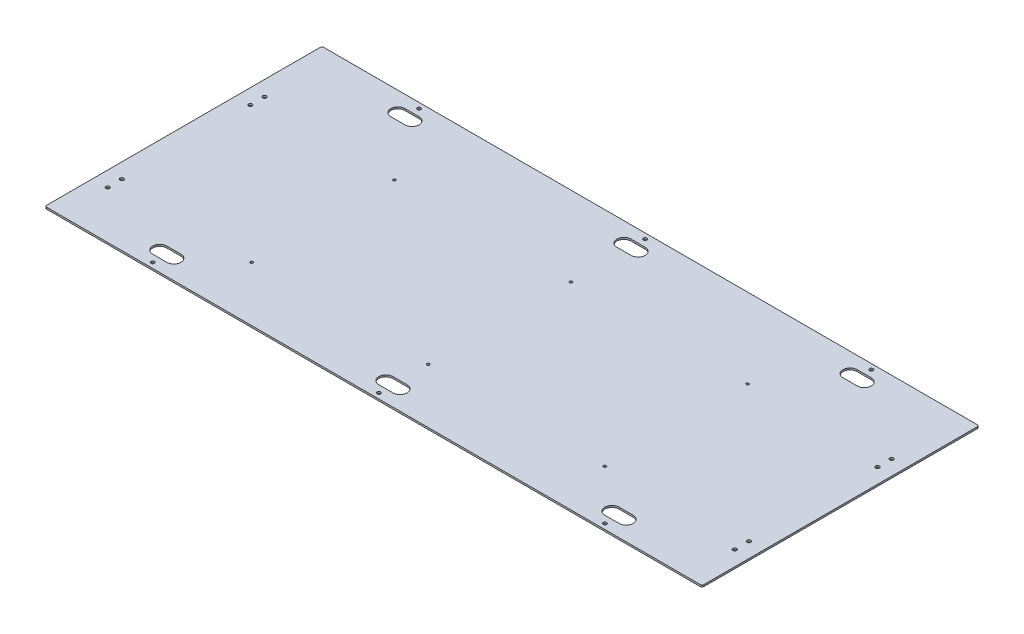
SolidWorks part; units mm, degrees
material "PE High Density"
ref_plane "Front Plane" through (0, 0, 0) normal (0, 0, 1) x (1, 0, 0)
ref_plane "Top Plane" through (0, 0, 0) normal (0, 1, 0) x (1, 0, 0)
ref_plane "Right Plane" through (0, 0, 0) normal (1, 0, 0) x (0, 0, -1)
sketch "Sketch1" plane through (0, 0, 0) normal (0, 1, 0) x (1, 0, 0)
  line L1 (-587.375, -248.92) -> (587.375, -248.92)
  line L2 (-590.55, -245.745) -> (-590.55, 245.745)
  line L3 (-587.375, 248.92) -> (587.375, 248.92)
  line L4 (590.55, -245.745) -> (590.55, 245.745)
  line L5 (-590.55, -248.92) -> (590.55, 248.92) construction
  line L6 (-590.55, 248.92) -> (590.55, -248.92) construction
  arc A0 (587.375, 248.92) -> (590.55, 245.745) centre (587.375, 245.745) cw
  arc A1 (587.375, -248.92) -> (590.55, -245.745) centre (587.375, -245.745) ccw
  arc A2 (-587.375, -248.92) -> (-590.55, -245.745) centre (-587.375, -245.745) cw
  arc A3 (-590.55, 245.745) -> (-587.375, 248.92) centre (-587.375, 245.745) cw
  point P0 (0, 0)
  dimension "D3" = 3.175
  dimension "D1" = 1181.1
  dimension "D2" = 497.84
extrude "Boss-Extrude1" add sketch "Sketch1" along normal blind 3.175
sketch "Sketch2" plane through (0, 3.175, 0) normal (0, 1, 0) x (1, 0, 0)
  line L0 (-590.55, 245.745) -> (-590.55, -245.745) construction
  line L1 (590.55, -245.745) -> (590.55, 245.745) construction
  line L2 (587.375, 248.92) -> (-587.375, 248.92) construction
  line L3 (-587.375, -248.92) -> (587.375, -248.92) construction
  point P0 (-406.4, 239.395)
  point P2 (0, 239.395)
  point P4 (406.4, 239.395)
  point P5 (-406.4, -239.395)
  point P7 (0, -239.395)
  point P9 (406.4, -239.395)
  point P16 (0, 106.045)
  point P17 (-317.5, 106.045)
  point P20 (317.5, 106.045)
  point P21 (-317.5, -150.495)
  point P24 (0, -150.495)
  point P25 (317.5, -150.495)
  dimension "D1" = 184.15
  dimension "D2" = 184.15
  dimension "D3" = 9.525
  dimension "D4" = 9.525
  dimension "D5" = 406.4
  dimension "D6" = 317.5
  dimension "D7" = 317.5
  dimension "D8" = 106.045
  dimension "D9" = 150.495
hole_wizard "1/4 (0.25) Diameter Hole1" positions "Sketch3" profile "Sketch4" hole size "1/4" standard "ANSI Inch" end condition through all
sketch "Sketch3" plane through (0, 3.175, 0) normal (0, 1, 0) x (1, 0, 0)
  point P3 (-406.4, 239.395)
  point P9 (0, 239.395)
  point P15 (406.4, 239.395)
  point P27 (406.4, -239.395)
  point P33 (0, -239.395)
  point P39 (-406.4, -239.395)
sketch "Sketch4" plane through (-406.4, 3.175, -239.395) normal (1, 0, 0) x (0, 0, 1)
  line L0 (0, 0) -> (0, 3.175)
  line L1 (0, 3.175) -> (3.175, 3.175)
  line L2 (3.175, 3.175) -> (3.175, 0)
  line L5 (3.175, 0) -> (0, 0)
  line L11 (0, -6.35) -> (0, 107.95) construction
  dimension "Thru Hole Dia." = 6.35
  dimension "Thru Hole Depth" = 3.175
sketch "Sketch5" plane through (0, 3.175, 0) normal (0, 1, 0) x (1, 0, 0)
  line L0 (-419.1, 213.995) -> (-393.7, 213.995) construction
  line L1 (-419.1, 226.695) -> (-393.7, 226.695)
  line L2 (-419.1, 201.295) -> (-393.7, 201.295)
  line L6 (-12.7, 213.995) -> (12.7, 213.995) construction
  line L7 (-12.7, 226.695) -> (12.7, 226.695)
  line L8 (-12.7, 201.295) -> (12.7, 201.295)
  line L9 (590.55, -245.745) -> (590.55, 245.745) construction
  line L12 (393.7, 213.995) -> (419.1, 213.995) construction
  line L13 (393.7, 226.695) -> (419.1, 226.695)
  line L14 (393.7, 201.295) -> (419.1, 201.295)
  line L15 (-419.1, -213.995) -> (-393.7, -213.995) construction
  line L16 (-419.1, -201.295) -> (-393.7, -201.295)
  line L17 (-419.1, -226.695) -> (-393.7, -226.695)
  line L21 (-12.7, -213.995) -> (12.7, -213.995) construction
  line L22 (-12.7, -201.295) -> (12.7, -201.295)
  line L23 (-12.7, -226.695) -> (12.7, -226.695)
  line L27 (393.7, -213.995) -> (419.1, -213.995) construction
  line L28 (393.7, -201.295) -> (419.1, -201.295)
  line L29 (393.7, -226.695) -> (419.1, -226.695)
  line L31 (-590.55, 245.745) -> (-590.55, -245.745) construction
  arc A0 (-419.1, 226.695) -> (-419.1, 201.295) centre (-419.1, 213.995) ccw
  arc A1 (-393.7, 201.295) -> (-393.7, 226.695) centre (-393.7, 213.995) ccw
  arc A4 (-12.7, 226.695) -> (-12.7, 201.295) centre (-12.7, 213.995) ccw
  arc A5 (12.7, 201.295) -> (12.7, 226.695) centre (12.7, 213.995) ccw
  arc A8 (393.7, 226.695) -> (393.7, 201.295) centre (393.7, 213.995) ccw
  arc A9 (419.1, 201.295) -> (419.1, 226.695) centre (419.1, 213.995) ccw
  arc A10 (-419.1, -201.295) -> (-419.1, -226.695) centre (-419.1, -213.995) ccw
  arc A11 (-393.7, -226.695) -> (-393.7, -201.295) centre (-393.7, -213.995) ccw
  arc A14 (-12.7, -201.295) -> (-12.7, -226.695) centre (-12.7, -213.995) ccw
  arc A15 (12.7, -226.695) -> (12.7, -201.295) centre (12.7, -213.995) ccw
  arc A18 (393.7, -201.295) -> (393.7, -226.695) centre (393.7, -213.995) ccw
  arc A19 (419.1, -226.695) -> (419.1, -201.295) centre (419.1, -213.995) ccw
  circle A20 centre (-406.4, 239.395) radius 3.175 construction
  circle A21 centre (-406.4, -239.395) radius 3.175 construction
  circle A22 centre (0, 239.395) radius 3.175 construction
  circle A23 centre (406.4, 239.395) radius 3.175 construction
  circle A24 centre (406.4, -239.395) radius 3.175 construction
  point P2 (-406.4, 213.995)
  point P16 (0, 213.995)
  point P30 (406.4, 213.995)
  point P37 (-406.4, -213.995)
  point P51 (0, -213.995)
  point P65 (406.4, -213.995)
  dimension "D1" = 12.7
  dimension "D2" = 12.7
  dimension "D11" = 12.7
  dimension "D3" = 25.4
  dimension "D4" = 25.4
  dimension "D5" = 184.15
  dimension "D6" = 406.4
  dimension "D7" = 406.4
  dimension "D8" = 406.4
  dimension "D9" = 406.4
  dimension "D10" = 184.15
  dimension "D12" = 12.7
  dimension "D13" = 12.7
  dimension "D14" = 184.15
extrude "Cut-Extrude1" cut sketch "Sketch5" against normal through all
hole_wizard "#10 (0.1935) Diameter Hole7" positions "3DSketch2" profile "Sketch10" hole size "#10" standard "ANSI Inch" end condition through all
sketch3d "3DSketch2"
  point P0 (-317.5, 3.175, -106.045)
  point P3 (0, 3.175, -106.045)
  point P12 (317.5, 3.175, -106.045)
  point P15 (317.5, 3.175, 150.495)
  point P18 (0, 3.175, 150.495)
  point P27 (-317.5, 3.175, 150.495)
sketch "Sketch10" plane through (-317.5, 3.175, -106.045) normal (1, 0, 0) x (0, 0, 1)
  line L0 (0, 0) -> (0, 3.175)
  line L1 (0, 3.175) -> (2.4574, 3.175)
  line L2 (2.4574, 3.175) -> (2.4574, 0)
  line L5 (2.4574, 0) -> (0, 0)
  line L11 (0, -6.35) -> (0, 107.95) construction
  dimension "Thru Hole Dia." = 4.9149
  dimension "Thru Hole Depth" = 3.175
sketch "Sketch11" plane through (0, 3.175, 0) normal (0, 1, 0) x (1, 0, 0)
  line L0 (-590.55, 245.745) -> (-590.55, -245.745) construction
  line L1 (-563.5625, 118.745) -> (563.5625, 118.745) construction
  line L2 (-563.5625, 118.745) -> (-563.5625, -163.195) construction
  line L3 (-563.5625, -163.195) -> (563.5625, -163.195) construction
  line L4 (563.5625, 118.745) -> (563.5625, -163.195) construction
  line L5 (-563.5625, 118.745) -> (563.5625, -163.195) construction
  line L6 (-563.5625, -163.195) -> (563.5625, 118.745) construction
  line L8 (563.5625, -137.795) -> (-563.5625, -137.795) construction
  line L9 (563.5625, -137.795) -> (563.5625, 93.345) construction
  line L10 (563.5625, 93.345) -> (-563.5625, 93.345) construction
  line L11 (-563.5625, -137.795) -> (-563.5625, 93.345) construction
  line L12 (563.5625, -137.795) -> (-563.5625, 93.345) construction
  line L13 (563.5625, 93.345) -> (-563.5625, -137.795) construction
  point P0 (0, -22.225)
  point P9 (0, -22.225)
  dimension "D1" = 26.9875
  dimension "D2" = 281.94
  dimension "D3" = 25.4
  dimension "D4" = 22.225
hole_wizard "17/64 (0.26563) Diameter Hole1" positions "Sketch12" profile "Sketch13" hole size "17/64" standard "ANSI Inch" end condition up to next
sketch "Sketch12" plane through (0, 3.175, 0) normal (0, 1, 0) x (1, 0, 0)
  point P0 (-563.5625, 118.745)
  point P3 (-563.5625, 93.345)
  point P6 (-563.5625, -137.795)
  point P9 (-563.5625, -163.195)
  point P12 (563.5625, -163.195)
  point P15 (563.5625, -137.795)
  point P18 (563.5625, 118.745)
  point P21 (563.5625, 93.345)
sketch "Sketch13" plane through (-563.5625, 3.175, -118.745) normal (1, 0, 0) x (0, 0, 1)
  line L0 (0, 0) -> (0, 3.175)
  line L1 (0, 3.175) -> (3.3735, 3.175)
  line L2 (3.3735, 3.175) -> (3.3735, 0)
  line L5 (3.3735, 0) -> (0, 0)
  line L11 (0, -6.35) -> (0, 107.95) construction
  dimension "Thru Hole Dia." = 6.747
  dimension "Thru Hole Depth" = 3.175
